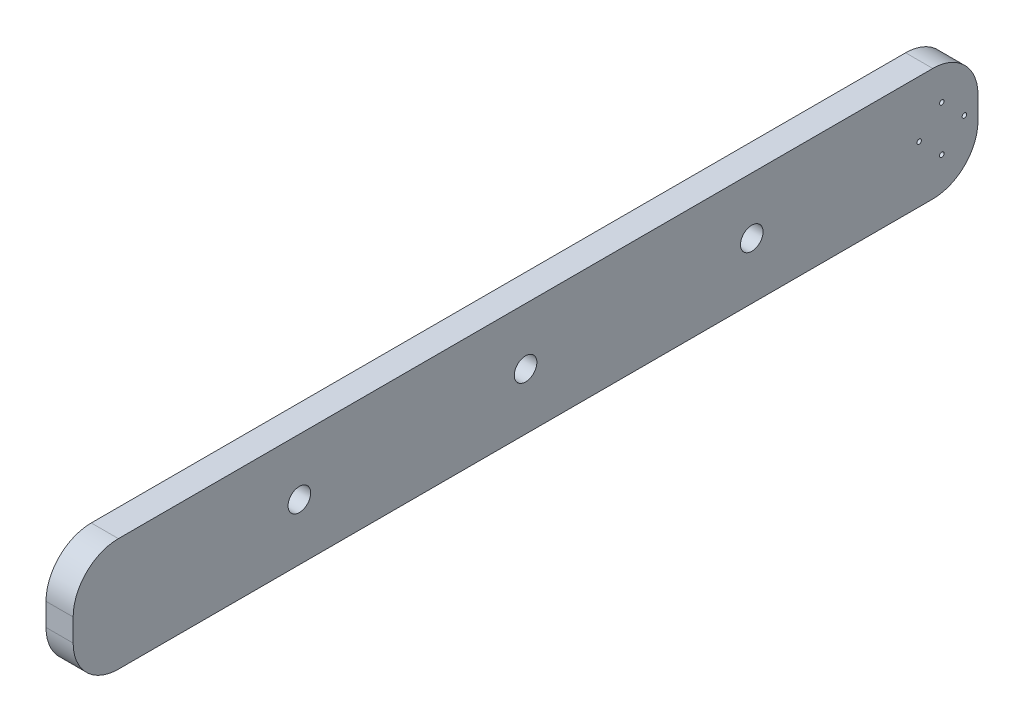
SolidWorks part; units mm, degrees
ref_plane "Plan de face" through (0, 0, 0) normal (0, 0, 1) x (1, 0, 0)
ref_plane "Plan de dessus" through (0, 0, 0) normal (0, 1, 0) x (1, 0, 0)
ref_plane "Plan de droite" through (0, 0, 0) normal (1, 0, 0) x (0, 0, -1)
sketch "Esquisse1" plane through (0, 0, 0) normal (1, 0, 0) x (0, 0, -1)
  line L1 (90, -12.5) -> (-90, -12.5)
  line L2 (100, -2.5) -> (100, 2.5)
  line L3 (90, 12.5) -> (-90, 12.5)
  line L4 (-100, -2.5) -> (-100, 2.5)
  arc A0 (100, -2.5) -> (90, -12.5) centre (90, -2.5) cw
  arc A1 (90, 12.5) -> (100, 2.5) centre (90, 2.5) cw
  arc A2 (-90, 12.5) -> (-100, 2.5) centre (-90, 2.5) ccw
  arc A3 (-90, -12.5) -> (-100, -2.5) centre (-90, -2.5) cw
  point P7 (100, -12.5)
  point P12 (-100, 12.5)
  point P15 (-100, -12.5)
  dimension "D5" = 10
  dimension "D6" = 10
  dimension "D7" = 10
  dimension "D8" = 10
  dimension "D1" = 200
  dimension "D2" = 25
  dimension "D3" = 12.5
  dimension "D4" = 100
extrude "Boss.-Extru.1" add sketch "Esquisse1" along normal blind 6
sketch "Esquisse2" plane through (0, 0, 0) normal (-1, 0, 0) x (0, 0, 1)
  line L0 (-157.7863, 0) -> (153.195, 0) construction
  line L1 (-92, 62.0354) -> (-92, -78.414) construction
  line L2 (-100, -2.5) -> (-100, 2.5) construction
  line L3 (100, 2.5) -> (100, -2.5) construction
  circle A0 centre (-97, 0) radius 0.5
  circle A1 centre (-92, 5) radius 0.5
  circle A2 centre (-92, -5) radius 0.5
  circle A3 centre (-87, 0) radius 0.5
  circle A4 centre (-50, 0) radius 2.5
  circle A5 centre (0, 0) radius 2.5
  circle A6 centre (50, 0) radius 2.5
  dimension "D2" = 1
  dimension "D3" = 1
  dimension "D4" = 5
  dimension "D5" = 5
  dimension "D6" = 50
  dimension "D7" = 50
  dimension "D8" = 50
  dimension "D9" = 5
  dimension "D10" = 5
  dimension "D11" = 5
  dimension "D12" = 50
  dimension "D1" = 8
extrude "Enlèv. mat.-Extru.1" cut sketch "Esquisse2" against normal blind 6
